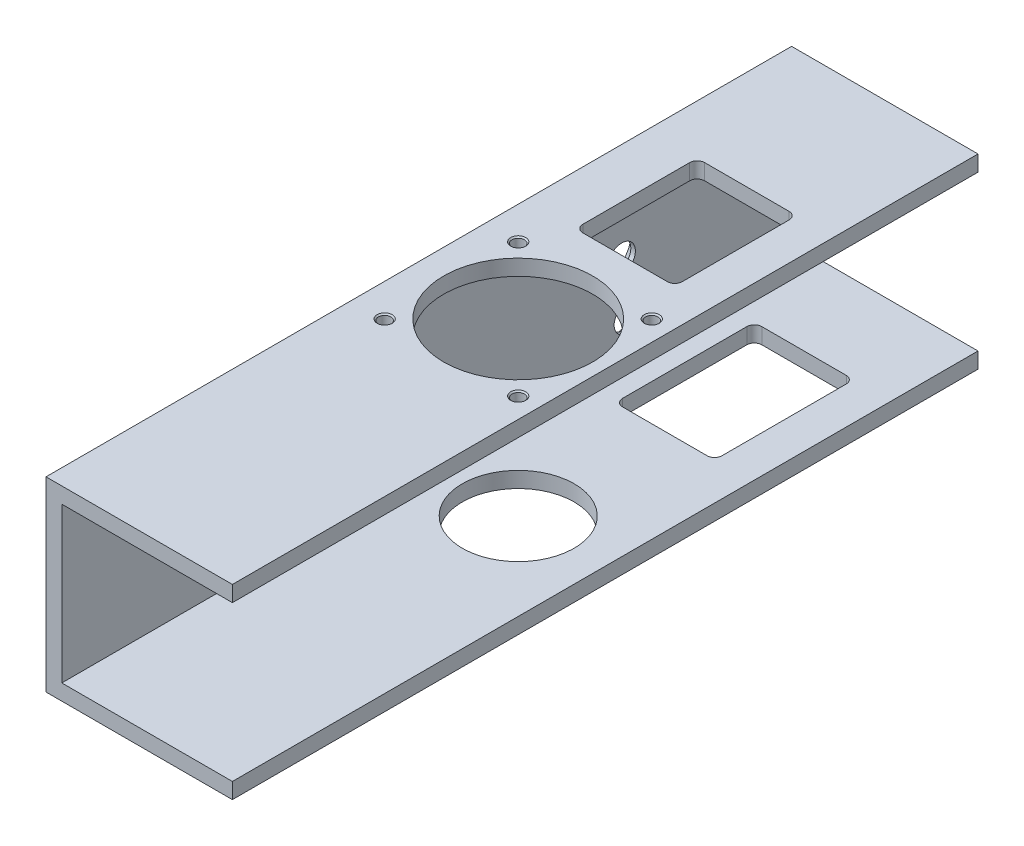
SolidWorks part; units mm, degrees
ref_plane "Front Plane" through (0, 0, 0) normal (0, 0, 1) x (1, 0, 0)
ref_plane "Top Plane" through (0, 0, 0) normal (0, 1, 0) x (1, 0, 0)
ref_plane "Right Plane" through (0, 0, 0) normal (1, 0, 0) x (0, 0, -1)
sketch "Sketch1" plane through (0, 0, 0) normal (0, 0, 1) x (1, 0, 0)
  line L0 (0, -37.5) -> (0, 37.5)
  line L1 (0, 37.5) -> (75, 37.5)
  line L2 (75, 37.5) -> (75, 31.15)
  line L3 (75, 31.15) -> (6.35, 31.15)
  line L4 (6.35, 31.15) -> (6.35, -31.15)
  line L5 (6.35, -31.15) -> (75, -31.15)
  line L6 (75, -31.15) -> (75, -37.5)
  line L7 (75, -37.5) -> (0, -37.5)
  line L8 (0, 0) -> (6.35, 0) construction
  dimension "D1" = 75
  dimension "D2" = 75
  dimension "D3" = 6.35
extrude "Boss-Extrude1" add sketch "Sketch1" along normal blind 300
sketch "Sketch2" plane through (0, 37.5, 0) normal (0, 1, 0) x (1, 0, 0)
  line L0 (0, -300) -> (0, 0) construction
  line L1 (75, -300) -> (0, -300) construction
  circle A0 centre (40, -150) radius 30
  dimension "D1" = 60
  dimension "D2" = 40
  dimension "D3" = 150
extrude "Cut-Extrude1" cut sketch "Sketch2" against normal through all
sketch "Sketch3" plane through (0, -37.5, 0) normal (0, -1, 0) x (1, 0, 0)
  line L0 (20, 91) -> (20, 35)
  line L1 (20, 91) -> (60, 91)
  line L2 (20, 35) -> (60, 35)
  line L3 (60, 91) -> (60, 35)
  line L4 (20, 91) -> (60, 35) construction
  line L5 (20, 35) -> (60, 91) construction
  line L6 (40, 91) -> (40, 150) construction
  circle A0 centre (40, 150) radius 30 construction
  point P1 (40, 63)
  dimension "D1" = 59
  dimension "D2" = 40
  dimension "D3" = 56
extrude "Cut-Extrude2" cut sketch "Sketch3" against normal blind 10
sketch "Sketch4" plane through (0, 37.5, 0) normal (0, 1, 0) x (1, 0, 0)
  line L0 (60, -107) -> (60, -58)
  line L1 (60, -107) -> (20, -107)
  line L2 (60, -58) -> (20, -58)
  line L3 (20, -107) -> (20, -58)
  line L4 (60, -107) -> (20, -58) construction
  line L5 (60, -58) -> (20, -107) construction
  line L6 (40, -107) -> (40, -150) construction
  circle A0 centre (40, -150) radius 30 construction
  point P1 (40, -82.5)
  dimension "D1" = 92
  dimension "D2" = 43
  dimension "D3" = 40
extrude "Cut-Extrude3" cut sketch "Sketch4" against normal blind 10
fillet "Fillet1" radius 3 8 edges at (60, -34.325, 35) (60, -34.325, 91) (20, -34.325, 91) (20, -34.325, 35) (60, 34.325, 107) (60, 34.325, 58) (20, 34.325, 58) (20, 34.325, 107)
hole_wizard "CSK for M10 Countersunk Flat Head Screw1" positions "Sketch6" profile "Sketch5" countersink size "M10" standard "ISO"
sketch "Sketch6" plane through (0, 0, 0) normal (-1, 0, 0) x (0, 0, 1)
  point P0 (74.7041, 4.0111)
  point P5 (72.25, -17.6)
sketch "Sketch5" plane through (0, 4.0111, 74.7041) normal (0, 1, 0) x (0, 0, 1)
  line L0 (0, 0) -> (0, 23.3077)
  line L1 (0, 23.3077) -> (5.5, 20.003)
  line L2 (5.5, 20.003) -> (5.5, 4.5)
  line L3 (5.5, 4.5) -> (10, 0)
  line L5 (10, 0) -> (0, 0)
  line L6 (-5.5, 4.5) -> (-10, 0) construction
  line L10 (0, 23.3077) -> (-5.5, 20.003) construction
  line L11 (0, -6.35) -> (0, 107.95) construction
  dimension "Hole Dia." = 11
  dimension "Hole Depth" = 20.003
  dimension "Near C'Sink Dia." = 20
  dimension "Near C'Sink Angle" = 90
  dimension "Drill Angle" = 118
sketch "Sketch7" plane through (0, -37.5, 0) normal (0, -1, 0) x (1, 0, 0)
  circle A0 centre (40, 150) radius 22.5
  circle A1 centre (40, 150) radius 30 construction
  circle A2 centre (40, 150) radius 30
  dimension "D1" = 45
extrude "Boss-Extrude2" add sketch "Sketch7" against normal up to surface (6.35 mm away) up to face at (40, -31.15, 63)
hole_wizard "M6x1.0 Tapped Hole1" positions "Sketch10" profile "Sketch9" tap size "M6x1.0" standard "BSI"
sketch "Sketch10" plane through (0, 37.5, 0) normal (0, 1, 0) x (1, 0, 0)
  line L0 (13.1299, -176.8701) -> (66.8701, -176.8701)
  line L1 (13.1299, -176.8701) -> (13.1299, -123.1299)
  line L2 (66.8701, -176.8701) -> (66.8701, -123.1299)
  line L3 (13.1299, -123.1299) -> (66.8701, -123.1299)
  line L4 (13.1299, -176.8701) -> (66.8701, -123.1299) construction
  line L5 (66.8701, -176.8701) -> (13.1299, -123.1299) construction
  circle A0 centre (40, -150) radius 38
  point P0 (66.8701, -123.1299)
  point P2 (13.1299, -123.1299)
  point P4 (13.1299, -176.8701)
  point P6 (66.8701, -176.8701)
  dimension "D1" = 76
sketch "Sketch9" plane through (66.8701, 37.5, 123.1299) normal (1, 0, 0) x (0, 0, 1)
  line L0 (0, 0) -> (0, 16.5022)
  line L1 (0, 16.5022) -> (2.5, 15)
  line L2 (2.5, 15) -> (2.5, 0.525)
  line L3 (2.5, 0.525) -> (3.025, 0)
  line L5 (3.025, 0) -> (0, 0)
  line L6 (-2.5, 0.525) -> (-3.025, 0) construction
  line L10 (0, 16.5022) -> (-2.5, 15) construction
  line L11 (0, -6.35) -> (0, 107.95) construction
  dimension "Tap Drill Dia." = 5
  dimension "Tap Drill Depth" = 15
  dimension "Near C'Sink Dia." = 6.05
  dimension "Near C'Sink Angle" = 90
  dimension "Drill Angle" = 118
cosmetic thread "Hole Thread1" parameters "D1"=6.35, "D2"=6
cosmetic thread "Hole Thread2" parameters "D1"=6.35, "D2"=6
cosmetic thread "Hole Thread3" parameters "D1"=6.35, "D2"=6
cosmetic thread "Hole Thread4" parameters "D1"=6.35, "D2"=6
